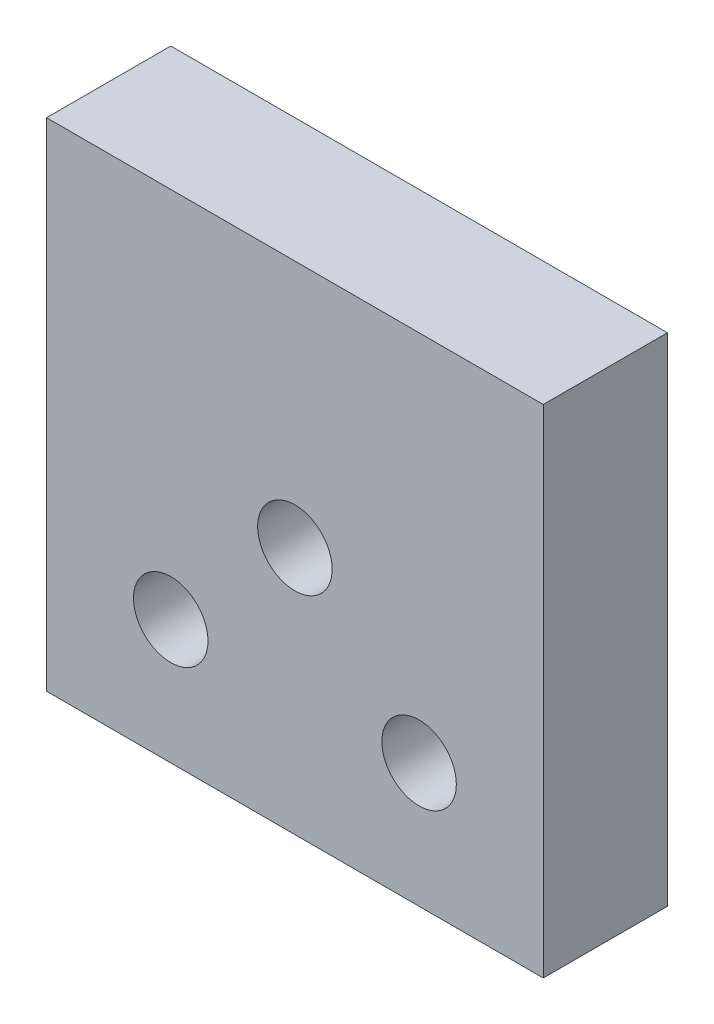
SolidWorks part; units mm, degrees
ref_plane "前视基准面" through (0, 0, 0) normal (0, 0, 1) x (1, 0, 0)
ref_plane "上视基准面" through (0, 0, 0) normal (0, 1, 0) x (1, 0, 0)
ref_plane "右视基准面" through (0, 0, 0) normal (1, 0, 0) x (0, 0, -1)
sketch "草图1" plane through (0, 0, 0) normal (0, 0, 1) x (1, 0, 0)
  line L1 (10, -10) -> (-10, -10)
  line L2 (10, -10) -> (10, 10)
  line L3 (10, 10) -> (-10, 10)
  line L4 (-10, -10) -> (-10, 10)
  line L5 (10, -10) -> (-10, 10) construction
  line L6 (10, 10) -> (-10, -10) construction
  circle A0 centre (0, 0) radius 1.5
  point P0 (0, 0)
  dimension "D3" = 3
  dimension "D1" = 20
  dimension "D2" = 20
extrude "凸台-拉伸1" add sketch "草图1" along normal blind 5
sketch "草图2" plane through (0, 0, 5) normal (0, 0, 1) x (1, 0, 0)
  line L0 (-10, 10) -> (-10, -10) construction
  line L2 (-10, -10) -> (10, -10) construction
  circle A0 centre (-5, -5) radius 1.5
  circle A1 centre (5, -5) radius 1.5
  point P6 (0, 0)
  dimension "D1" = 3
  dimension "D2" = 3
  dimension "D3" = 10
  dimension "D4" = 5
  dimension "D5" = 5
extrude "切除-拉伸1" cut sketch "草图2" against normal blind 10
